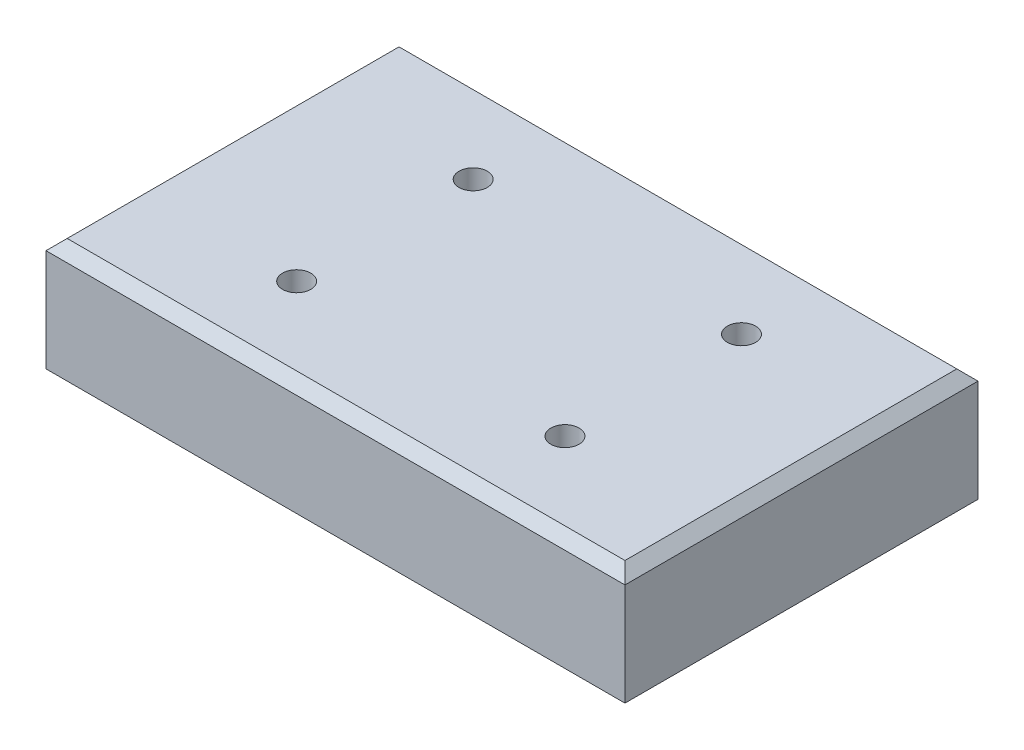
SolidWorks part; units mm, degrees
ref_plane "Front Plane" through (0, 0, 0) normal (0, 0, 1) x (1, 0, 0)
ref_plane "Top Plane" through (0, 0, 0) normal (0, 1, 0) x (1, 0, 0)
ref_plane "Right Plane" through (0, 0, 0) normal (1, 0, 0) x (0, 0, -1)
sketch "Sketch1" plane through (0, 0, 0) normal (0, 1, 0) x (1, 0, 0)
  line L1 (41, 25) -> (-41, 25)
  line L2 (41, 25) -> (41, -25)
  line L3 (41, -25) -> (-41, -25)
  line L4 (-41, 25) -> (-41, -25)
  line L5 (41, 25) -> (-41, -25) construction
  line L6 (41, -25) -> (-41, 25) construction
  point P0 (0, 0)
  dimension "D1" = 82
  dimension "D2" = 50
extrude "Boss-Extrude1" add sketch "Sketch1" along normal mid plane 16
chamfer "Chamfer1" distance 1.5 angle 45 4 edges at (-41, 8, 0) (0, 8, -25) (41, 8, 0) (0, 8, 25)
hole_wizard "CBORE for M5 Hex Head Bolt1" positions "Sketch2" profile "Sketch3" counterbore size "M5" standard "ISO"
sketch "Sketch2" plane through (0, 8, 0) normal (0, 1, 0) x (1, 0, 0)
  line L0 (-41, -25) -> (-41, 25) construction
  line L1 (-41, 25) -> (41, 25) construction
  point P0 (-18, 12.5)
  point P2 (-18, -12.5)
  point P4 (20, -12.5)
  point P6 (20, 12.5)
  dimension "D1" = 38
  dimension "D2" = 25
  dimension "D3" = 23
  dimension "D4" = 12.5
sketch "Sketch3" plane through (-18, 8, -12.5) normal (1, 0, 0) x (0, 0, 1)
  line L0 (0, 0) -> (0, 8.9013)
  line L1 (0, 8.9013) -> (1.5, 8)
  line L2 (1.5, 8) -> (1.5, 6)
  line L3 (1.5, 6) -> (2, 6)
  line L4 (2, 6) -> (2, 0)
  line L5 (2, 0) -> (0, 0)
  line L10 (0, 8.9013) -> (-1.5, 8) construction
  line L11 (0, -6.35) -> (0, 107.95) construction
  dimension "Hole Dia." = 3
  dimension "Hole Depth" = 8
  dimension "C'Bore Dia." = 4
  dimension "C'Bore Depth" = 6
  dimension "Drill Angle" = 118
